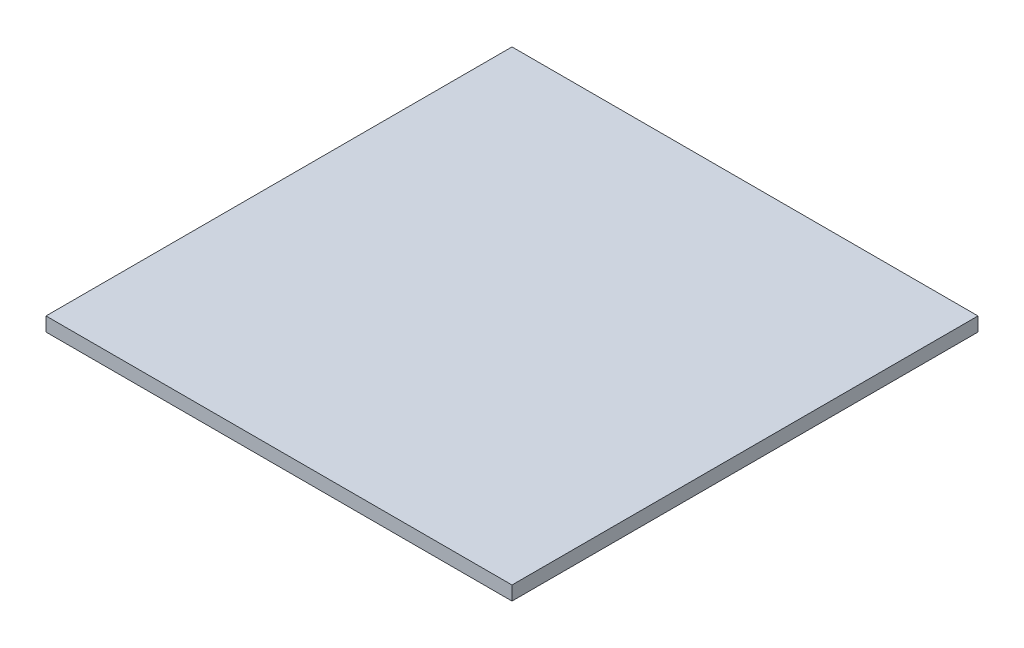
SolidWorks part; units mm, degrees
ref_plane "Front Plane" through (0, 0, 0) normal (0, 0, 1) x (1, 0, 0)
ref_plane "Top Plane" through (0, 0, 0) normal (0, 1, 0) x (1, 0, 0)
ref_plane "Right Plane" through (0, 0, 0) normal (1, 0, 0) x (0, 0, -1)
sketch "Sketch1" plane through (0, 0, 0) normal (0, 1, 0) x (1, 0, 0)
  line L1 (-103.4375, 107.1875) -> (-3.4375, 107.1875)
  line L2 (-103.4375, 107.1875) -> (-103.4375, 7.1875)
  line L3 (-103.4375, 7.1875) -> (-3.4375, 7.1875)
  line L4 (-3.4375, 107.1875) -> (-3.4375, 7.1875)
  dimension "D1" = 100
  dimension "D2" = 100
extrude "Boss-Extrude1" add sketch "Sketch1" along normal blind 3
